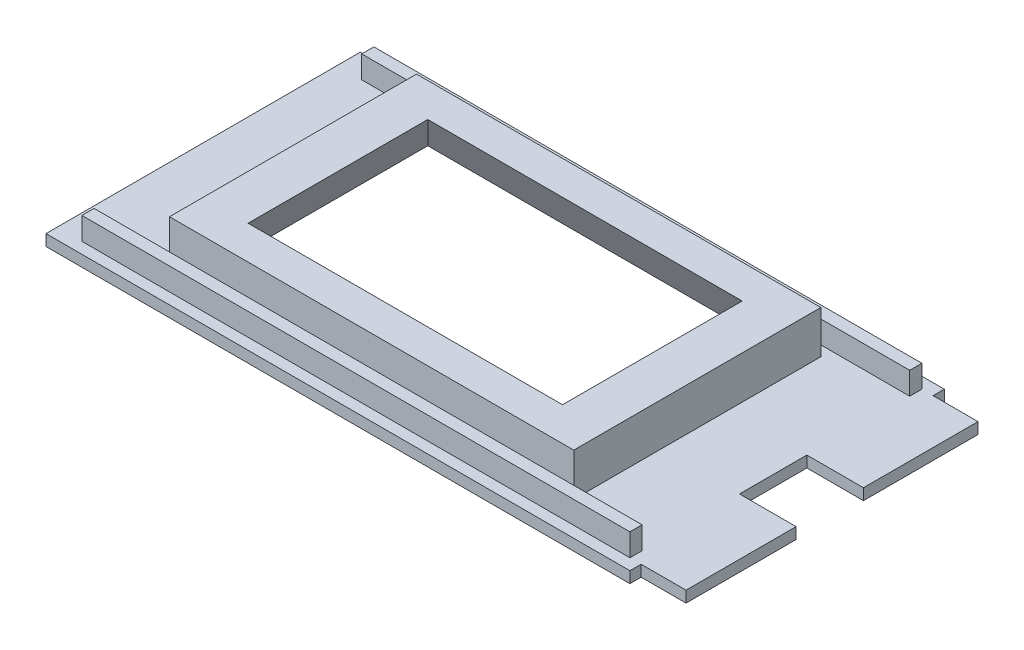
SolidWorks part; units mm, degrees
ref_plane "Front Plane" through (0, 0, 0) normal (0, 0, 1) x (1, 0, 0)
ref_plane "Top Plane" through (0, 0, 0) normal (0, 1, 0) x (1, 0, 0)
ref_plane "Right Plane" through (0, 0, 0) normal (1, 0, 0) x (0, 0, -1)
sketch "Sketch1" plane through (0, 0, 0) normal (0, 1, 0) x (1, 0, 0)
  line L1 (-82.55, -44.45) -> (82.55, -44.45)
  line L2 (-82.55, -44.45) -> (-82.55, 44.45)
  line L3 (-82.55, 44.45) -> (82.55, 44.45)
  line L4 (82.55, -44.45) -> (82.55, 44.45)
  line L5 (-82.55, -44.45) -> (82.55, 44.45) construction
  line L6 (-82.55, 44.45) -> (82.55, -44.45) construction
  point P0 (0, 0)
  dimension "D1" = 165.1
  dimension "D2" = 88.9
extrude "Boss-Extrude1" add sketch "Sketch1" along normal blind 3.175
sketch "Sketch3" plane through (82.55, 0, 0) normal (1, 0, 0) x (0, 0, -1)
  line L0 (-44.45, 3.175) -> (44.45, 3.175) construction
  line L1 (41.275, 3.175) -> (-41.275, 3.175)
  line L2 (41.275, 3.175) -> (41.275, 0)
  line L3 (41.275, 0) -> (-41.275, 0)
  line L4 (-41.275, 3.175) -> (-41.275, 0)
  line L5 (-44.45, 0) -> (44.45, 0) construction
  line L6 (44.45, 3.175) -> (44.45, 0) construction
  point P8 (41.275, 1.5875)
  dimension "D1" = 82.55
  dimension "D2" = 3.175
extrude "Boss-Extrude3" add sketch "Sketch3" along normal blind 12.7
sketch "Sketch6" plane through (95.25, 0, 0) normal (1, 0, 0) x (0, 0, -1)
  line L1 (8.89, 0) -> (-10.16, 0)
  line L2 (8.89, 0) -> (8.89, 3.175)
  line L3 (8.89, 3.175) -> (-10.16, 3.175)
  line L4 (-10.16, 0) -> (-10.16, 3.175)
  dimension "D1" = 19.05
extrude "Cut-Extrude1" cut sketch "Sketch6" against normal blind 16.002
sketch "Sketch8" plane through (0, 3.175, 0) normal (0, 1, 0) x (1, 0, 0)
  line L0 (82.55, 41.275) -> (82.55, 44.45) construction
  line L4 (-75.565, -37.8379) -> (79.375, -37.8379)
  line L5 (79.375, -41.275) -> (79.375, -37.8379)
  line L6 (-75.565, -41.275) -> (79.375, -41.275)
  line L7 (-75.565, -41.275) -> (-75.565, -37.8379)
  line L13 (-75.565, 41.275) -> (79.375, 41.275)
  line L14 (-75.565, 41.275) -> (-75.565, 37.8379)
  line L15 (-75.565, 37.8379) -> (79.375, 37.8379)
  line L16 (79.375, 41.275) -> (79.375, 37.8379)
  point P4 (79.375, 39.5565)
  point P7 (82.55, 42.8625)
  dimension "D1" = 154.94
  dimension "D2" = 3.175
extrude "Boss-Extrude4" add sketch "Sketch8" along normal blind 6.35
sketch "Sketch9" plane through (0, 0, 0) normal (0, 1, 0) x (1, 0, 0)
  line L1 (-57.15, 34.925) -> (57.15, 34.925)
  line L2 (-57.15, 34.925) -> (-57.15, -34.925)
  line L3 (-57.15, -34.925) -> (57.15, -34.925)
  line L4 (57.15, 34.925) -> (57.15, -34.925)
  line L5 (-57.15, 34.925) -> (57.15, -34.925) construction
  line L6 (-57.15, -34.925) -> (57.15, 34.925) construction
  point P0 (0, 0)
  dimension "D1" = 114.3
  dimension "D2" = 69.85
extrude "Boss-Extrude5" add sketch "Sketch9" along normal blind 15.24
sketch "Sketch12" plane through (0, 15.24, 0) normal (0, 1, 0) x (1, 0, 0)
  line L1 (-44.45, 25.4) -> (44.45, 25.4)
  line L2 (-44.45, 25.4) -> (-44.45, -25.4)
  line L3 (-44.45, -25.4) -> (44.45, -25.4)
  line L4 (44.45, 25.4) -> (44.45, -25.4)
  line L5 (-44.45, 25.4) -> (44.45, -25.4) construction
  line L6 (-44.45, -25.4) -> (44.45, 25.4) construction
  point P0 (0, 0)
  dimension "D1" = 88.9
  dimension "D2" = 50.8
extrude "Cut-Extrude2" cut sketch "Sketch12" against normal blind 15.24 draft 30 draft outward yes
